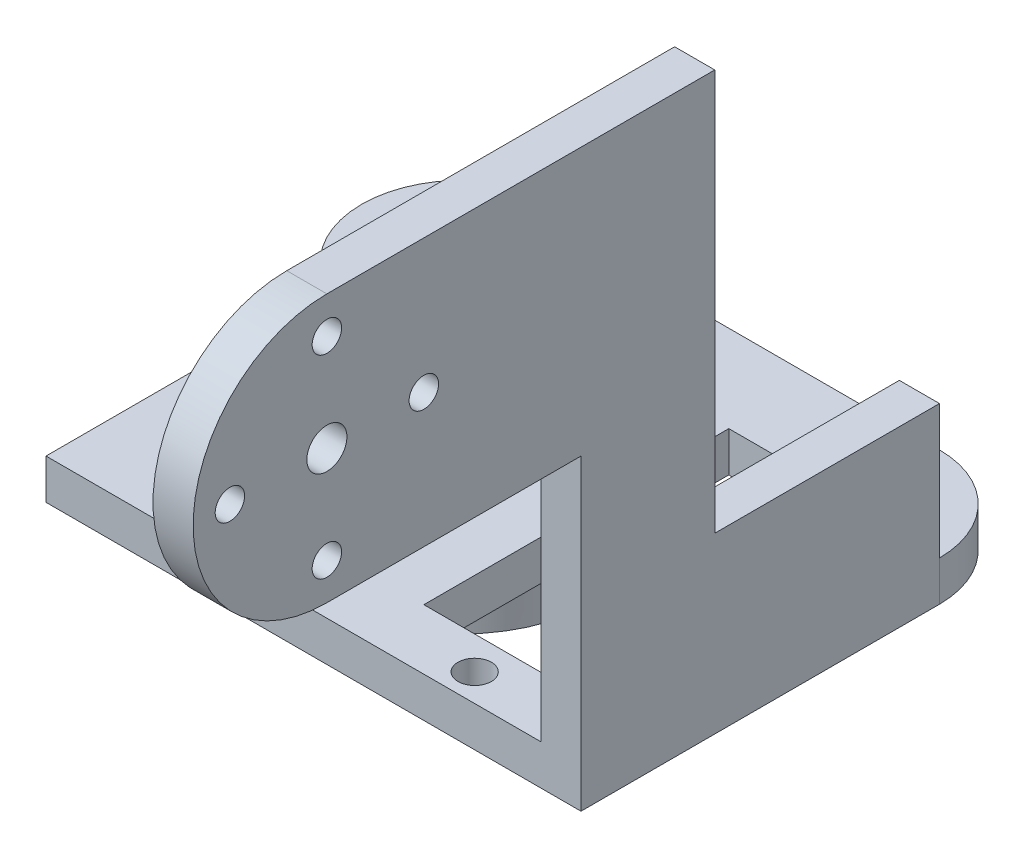
SolidWorks part; units mm, degrees
ref_plane "前视基准面" through (0, 0, 0) normal (0, 0, 1) x (1, 0, 0)
ref_plane "上视基准面" through (0, 0, 0) normal (0, 1, 0) x (1, 0, 0)
ref_plane "右视基准面" through (0, 0, 0) normal (1, 0, 0) x (0, 0, -1)
sketch "草图1" plane through (0, 0, 0) normal (0, 1, 0) x (1, 0, 0)
  line L0 (-20, 0) -> (20, 0) construction
  line L1 (-20, 15.9) -> (20, 15.9) construction
  line L2 (-20, 15.9) -> (-20, -15.9) construction
  line L3 (-20, -15.9) -> (20, -15.9)
  line L4 (20, 15.9) -> (20, -15.9) construction
  line L5 (-20, 15.9) -> (20, -15.9) construction
  line L6 (-20, -15.9) -> (20, 15.9) construction
  line L7 (10, 11.4) -> (10, -11.4) construction
  line L8 (3.75, 11.4) -> (16.25, 11.4)
  line L9 (3.75, 11.4) -> (3.75, -11.4)
  line L10 (3.75, -11.4) -> (16.25, -11.4)
  line L11 (16.25, 11.4) -> (16.25, -11.4)
  line L12 (0, 15.9) -> (0, -15.9) construction
  line L13 (10, 5.2) -> (-10, 5.2) construction
  line L14 (10, -13.85) -> (10, 13.85) construction
  line L15 (-20, -15.9) -> (-20, 10.9)
  line L16 (-15, 15.9) -> (15, 15.9) construction
  line L17 (20, 10.9) -> (20, -15.9)
  line L18 (-20, 10.9) -> (-13, 10.9) construction
  line L19 (-13, 10.9) -> (-13, 17.9) construction
  line L20 (20, 10.9) -> (13, 10.9) construction
  line L21 (13, 10.9) -> (13, 17.9) construction
  line L22 (-13, 17.9) -> (13, 17.9)
  circle A0 centre (10, 5.2) radius 1.5 construction
  circle A2 centre (-10, 5.2) radius 4.5
  circle A3 centre (10, 13.85) radius 1.25
  circle A4 centre (10, -13.85) radius 1.25
  arc A5 (-20, 10.9) -> (-15, 15.9) centre (-15, 10.9) cw construction
  arc A6 (15, 15.9) -> (20, 10.9) centre (15, 10.9) cw construction
  arc A7 (-20, 10.9) -> (-13, 17.9) centre (-13, 10.9) cw
  arc A8 (13, 17.9) -> (20, 10.9) centre (13, 10.9) cw
  point P0 (0, 0)
  point P23 (10, 0)
  point P31 (15, 10.9)
  dimension "D6" = 3
  dimension "D7" = 9
  dimension "D8" = 20
  dimension "D10" = 2.5
  dimension "D11" = 2.5
  dimension "D14" = 5
  dimension "D17" = 5
  dimension "D18" = 7
  dimension "D19" = 7
  dimension "D1" = 31.8
  dimension "D2" = 40
  dimension "D3" = 12.5
  dimension "D4" = 22.8
  dimension "D5" = 10.7
  dimension "D9" = 27.7
  dimension "D12" = 5
  dimension "D13" = 5
  dimension "D15" = 5
  dimension "D16" = 5
extrude "凸台-拉伸1" add sketch "草图1" along normal blind 3
sketch "草图3" plane through (0, 0, 0) normal (1, 0, 0) x (0, 0, -1)
  line L1 (-27.65, 33) -> (-42.15, 33) construction
  line L2 (-15.9, 3) -> (-15.9, 23)
  line L3 (-15.9, 23) -> (-34.9, 23)
  line L4 (-34.9, 23) -> (-34.9, 43) construction
  line L5 (-34.9, 43) -> (-5.9, 43)
  line L6 (-5.9, 43) -> (-5.9, 13)
  line L9 (-15.9, 3) -> (10.9, 3) construction
  line L10 (-15.9, 3) -> (10.9, 3)
  line L11 (-5.9, 13) -> (10.9, 13)
  line L12 (10.9, 13) -> (10.9, 3)
  line L13 (-34.9, 25.75) -> (-34.9, 40.25) construction
  arc A0 (-34.9, 23) -> (-34.9, 43) centre (-34.9, 33) cw
  circle A2 centre (-42.15, 33) radius 1.1
  circle A3 centre (-34.9, 40.25) radius 1.1
  circle A4 centre (-27.65, 33) radius 1.1
  circle A5 centre (-34.9, 25.75) radius 1.1
  circle A6 centre (-34.9, 33) radius 1.5
  point P13 (-34.9, 33)
  point P16 (-34.9, 33)
  dimension "D9" = 2.2
  dimension "D1" = 20
  dimension "D2" = 19
  dimension "D3" = 20
  dimension "D4" = 10
  dimension "D5" = 10
  dimension "D7" = 14.5
  dimension "D8" = 14.5
extrude "凸台-拉伸2" add sketch "草图3" against normal blind 3 from surface at 20 starting at face at (20, 1.5, 2.5)
sketch "草图4" plane through (0, 3, 0) normal (0, 1, 0) x (1, 0, 0)
  circle A0 centre (-10, 5.2) radius 4.5 construction
  circle A1 centre (-10, 5.2) radius 4.5
  circle A2 centre (-10, 5.2) radius 7.5
  dimension "D1" = 15
extrude "凸台-拉伸3" add sketch "草图4" along normal blind 7
sketch "草图5" plane through (0, 0, 0) normal (0, -1, 0) x (1, 0, 0)
  circle A0 centre (-10, -5.2) radius 7.5
  circle A1 centre (-10, -5.2) radius 10
  dimension "D1" = 15
  dimension "D2" = 20
extrude "凸台-拉伸4" add sketch "草图5" along normal blind 7
